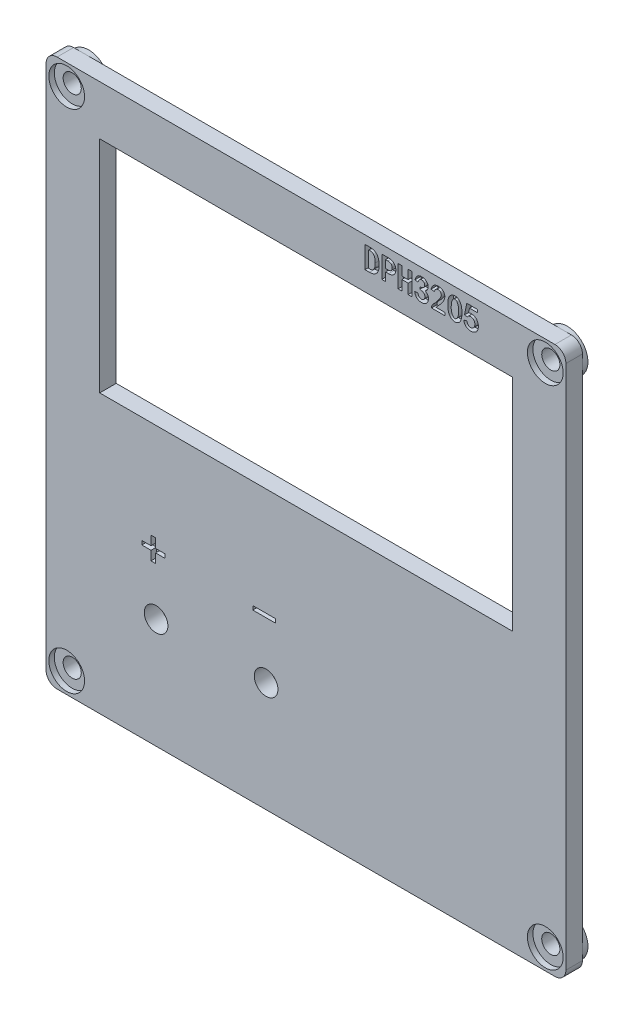
SolidWorks part; units mm, degrees
ref_plane "前视基准面" through (0, 0, 0) normal (0, 0, 1) x (1, 0, 0)
ref_plane "上视基准面" through (0, 0, 0) normal (0, 1, 0) x (1, 0, 0)
ref_plane "右视基准面" through (0, 0, 0) normal (1, 0, 0) x (0, 0, -1)
sketch "草图1" plane through (0, 0, 0) normal (0, 0, 1) x (1, 0, 0)
  line L0 (-27.25, -29.75) -> (-7.25, -29.75) construction
  line L1 (-45.25, -49.75) -> (45.25, -49.75)
  line L2 (-47.25, -47.75) -> (-47.25, 47.75)
  line L3 (-45.25, 49.75) -> (45.25, 49.75)
  line L4 (47.25, -47.75) -> (47.25, 47.75)
  line L5 (-47.25, -49.75) -> (47.25, 49.75) construction
  line L6 (-47.25, 49.75) -> (47.25, -49.75) construction
  line L7 (-37.5, 40.75) -> (37.5, 40.75)
  line L8 (-37.5, 40.75) -> (-37.5, 0.75)
  line L9 (-37.5, 0.75) -> (37.5, 0.75)
  line L10 (37.5, 40.75) -> (37.5, 0.75)
  arc A0 (-45.25, -49.75) -> (-47.25, -47.75) centre (-45.25, -47.75) cw
  arc A1 (45.25, -49.75) -> (47.25, -47.75) centre (45.25, -47.75) ccw
  arc A2 (45.25, 49.75) -> (47.25, 47.75) centre (45.25, 47.75) cw
  arc A3 (-47.25, 47.75) -> (-45.25, 49.75) centre (-45.25, 47.75) cw
  circle A4 centre (-27.25, -29.75) radius 2.15
  circle A5 centre (-7.25, -29.75) radius 2.15
  point P0 (0, 0)
  point P22 (0, 40.75)
  point P23 (0, 49.75)
  dimension "D3" = 2
  dimension "D10" = 4.3
  dimension "D1" = 99.5
  dimension "D2" = 94.5
  dimension "D4" = 75
  dimension "D5" = 40
  dimension "D6" = 9
  dimension "D7" = 20
  dimension "D8" = 20
  dimension "D9" = 20
extrude "凸台-拉伸1" add sketch "草图1" along normal blind 3
sketch "草图2" plane through (0, 0, 3) normal (0, 0, 1) x (1, 0, 0)
  text T0 "DPH3205" font "黑体" height 4
  text T1 "+" font "黑体" height 6
  text T2 "-" font "黑体" height 6
extrude "切除-拉伸1" cut sketch "草图2" against normal blind 1
sketch "草图3" plane through (0, 0, 0) normal (0, 0, -1) x (-1, 0, 0)
  line L0 (-45.25, 49.75) -> (45.25, 49.75) construction
  line L1 (43.5, -46) -> (-43.5, -46) construction
  line L2 (43.5, -46) -> (43.5, 46) construction
  line L3 (43.5, 46) -> (-43.5, 46) construction
  line L4 (-43.5, -46) -> (-43.5, 46) construction
  line L5 (43.5, -46) -> (-43.5, 46) construction
  line L6 (43.5, 46) -> (-43.5, -46) construction
  circle A0 centre (-43.5, 46) radius 3.75
  circle A1 centre (43.5, 46) radius 3.75
  circle A2 centre (43.5, -46) radius 3.75
  circle A3 centre (-43.5, -46) radius 3.75
  point P0 (0, 0)
  dimension "D1" = 87
  dimension "D2" = 92
extrude "凸台-拉伸2" add sketch "草图3" along normal blind 1
sketch "草图4" plane through (0, 0, -1) normal (0, 0, -1) x (-1, 0, 0)
  circle A0 centre (-43.5, 46) radius 1.65
  circle A1 centre (43.5, 46) radius 1.65
  circle A2 centre (43.5, -46) radius 1.65
  circle A3 centre (-43.5, -46) radius 1.65
  dimension "D1" = 3.3
extrude "切除-拉伸2" cut sketch "草图4" against normal through all
sketch "草图5" plane through (0, 0, 3) normal (0, 0, 1) x (1, 0, 0)
  circle A0 centre (-43.5, 46) radius 3.25
  circle A1 centre (43.5, 46) radius 3.25
  circle A2 centre (43.5, -46) radius 3.25
  circle A3 centre (-43.5, -46) radius 3.25
  dimension "D1" = 6.5
extrude "切除-拉伸3" cut sketch "草图5" against normal blind 1
